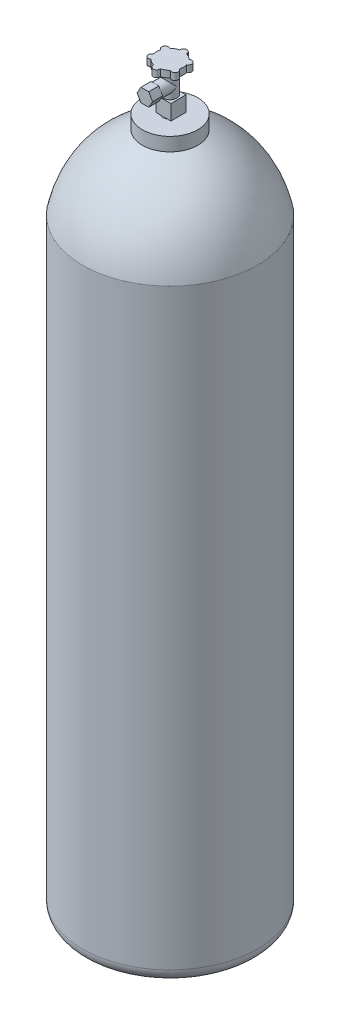
SolidWorks part; units mm, degrees
ref_plane "Front Plane" through (0, 0, 0) normal (0, 0, 1) x (1, 0, 0)
ref_plane "Top Plane" through (0, 0, 0) normal (0, 1, 0) x (1, 0, 0)
ref_plane "Right Plane" through (0, 0, 0) normal (1, 0, 0) x (0, 0, -1)
sketch "Sketch1" plane through (0, 0, 0) normal (0, 0, 1) x (1, 0, 0)
  line L0 (0, 0) -> (0, 1524) construction
  line L1 (0, 0) -> (165.1, 0)
  line L2 (165.1, 0) -> (165.1, 1143)
  line L3 (0, 1397) -> (25.4, 1397)
  line L4 (25.4, 1397) -> (25.4, 1384.3)
  line L5 (25.4, 1384.3) -> (12.7, 1384.3)
  line L6 (12.7, 1384.3) -> (12.7, 1308.1)
  line L7 (12.7, 1308.1) -> (52.3216, 1308.1)
  line L8 (52.3216, 1308.1) -> (52.3216, 1282.7)
  line L9 (0, 1397) -> (0, 0)
  spline S0 degree 2 poles (165.1, 1143) (143.6981, 1240.0838) (52.3216, 1282.7) knots 0 0 0 1 1 1
  dimension "D11" = 52.3216
  dimension "D1" = 1524
  dimension "D2" = 1143
  dimension "D3" = 25.4
  dimension "D4" = 12.7
  dimension "D5" = 25.4
  dimension "D6" = 76.2
  dimension "D7" = 25.4
  dimension "D8" = 1397
  dimension "D9" = 25.4
  dimension "D10" = 165.1
  dimension "D12" = 88.9
  dimension "D13" = 130.1661
  dimension "D14" = 86.7226
revolve "Revolve1" add sketch "Sketch1" angle 360 about L0
sketch "Sketch2" plane through (0, 1397, 0) normal (0, 1, 0) x (1, 0, 0)
  arc A0 (-18.1595, -17.7593) -> (-6.3002, -24.6062) centre (0, 0) ccw
  arc A1 (6.3002, 24.6062) -> (-6.3002, 24.6062) centre (0, 25.4) ccw
  arc A2 (24.4597, 6.847) -> (18.1595, 17.7593) centre (21.997, 12.7) ccw
  arc A3 (18.1595, -17.7593) -> (24.4597, -6.847) centre (21.997, -12.7) ccw
  arc A4 (-6.3002, -24.6062) -> (6.3002, -24.6062) centre (0, -25.4) ccw
  arc A5 (-24.4597, -6.847) -> (-18.1595, -17.7593) centre (-21.997, -12.7) ccw
  arc A6 (-18.1595, 17.7593) -> (-24.4597, 6.847) centre (-21.997, 12.7) ccw
  arc A7 (-24.4597, 6.847) -> (-24.4597, -6.847) centre (0, 0) ccw
  arc A8 (-6.3002, 24.6062) -> (-18.1595, 17.7593) centre (0, 0) ccw
  arc A9 (18.1595, 17.7593) -> (6.3002, 24.6062) centre (0, 0) ccw
  arc A10 (24.4597, -6.847) -> (24.4597, 6.847) centre (0, 0) ccw
  arc A11 (6.3002, -24.6062) -> (18.1595, -17.7593) centre (0, 0) ccw
  point P17 (0, 0)
  dimension "D1" = 12.7
  dimension "D2" = 6
extrude "Boss-Extrude1" add sketch "Sketch2" against normal blind 12.7
sketch "Sketch3" plane through (0, 0, 0) normal (1, 0, 0) x (0, 0, -1)
  line L0 (-12.7, 1384.3) -> (-12.7, 1308.1) construction
  line L1 (-14.2875, 1311.275) -> (14.2875, 1311.275)
  line L2 (-14.2875, 1311.275) -> (-14.2875, 1339.85)
  line L3 (-14.2875, 1339.85) -> (14.2875, 1339.85)
  line L4 (14.2875, 1311.275) -> (14.2875, 1339.85)
  line L5 (-14.2875, 1311.275) -> (14.2875, 1339.85) construction
  line L6 (-14.2875, 1339.85) -> (14.2875, 1311.275) construction
  line L7 (52.3216, 1308.1) -> (-52.3216, 1308.1) construction
  point P0 (0, 1325.5625)
  dimension "D1" = 28.575
  dimension "D2" = 28.575
  dimension "D3" = 1.5875
  dimension "D4" = 3.175
extrude "Boss-Extrude2" add sketch "Sketch3" along normal blind 28.575 from offset 12.7 offset against normal yes
sketch "Sketch4" plane through (0, 0, 0) normal (0, 0, 1) x (1, 0, 0)
  line L0 (15.875, 1339.85) -> (-12.7, 1339.85) construction
  line L2 (-12.7, 1384.3) -> (-12.7, 1339.85) construction
  circle A0 centre (0, 1358.9) radius 12.7
  dimension "D3" = 25.4
  dimension "D1" = 19.05
  dimension "D2" = 12.7
extrude "Boss-Extrude3" add sketch "Sketch4" along normal blind 28.575
sketch "Sketch5" plane through (0, 0, 28.575) normal (0, 0, 1) x (1, 0, 0)
  line L1 (14.6647, 1358.9) -> (7.3323, 1371.6)
  line L2 (7.3323, 1371.6) -> (-7.3323, 1371.6)
  line L3 (-7.3323, 1371.6) -> (-14.6647, 1358.9)
  line L4 (-14.6647, 1358.9) -> (-7.3323, 1346.2)
  line L5 (-7.3323, 1346.2) -> (7.3323, 1346.2)
  line L6 (7.3323, 1346.2) -> (14.6647, 1358.9)
  line L7 (12.7, 1339.85) -> (-12.7, 1339.85) construction
  circle A0 centre (0, 1358.9) radius 12.7 construction
  dimension "D1" = 25.4
extrude "Boss-Extrude4" add sketch "Sketch5" along normal blind 19.05
fillet "Fillet1" radius 25.4 1 edges at (0, 0, -165.1)
